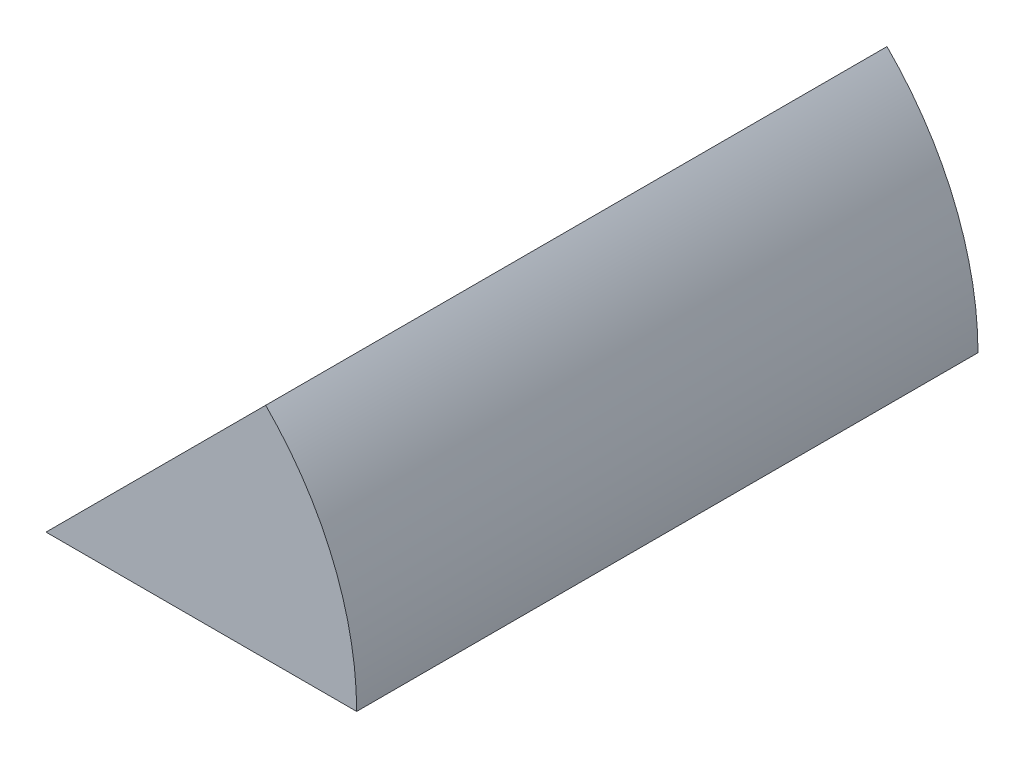
SolidWorks part; units mm, degrees
ref_plane "Alzado" through (0, 0, 0) normal (0, 0, 1) x (1, 0, 0)
ref_plane "Planta" through (0, 0, 0) normal (0, 1, 0) x (1, 0, 0)
ref_plane "Vista lateral" through (0, 0, 0) normal (1, 0, 0) x (0, 0, -1)
sketch "Croquis1" plane through (0, 0, 0) normal (0, 0, 1) x (1, 0, 0)
  line L1 (0, 0) -> (25, 0)
  line L2 (0, 0) -> (17.6777, 17.6777)
  arc A0 (25, 0) -> (17.6777, 17.6777) centre (0, 0) ccw
  dimension "D1" = 50
  dimension "D2" = 45
extrude "Saliente-Extruir1" add sketch "Croquis1" along normal blind 50
sketch "Croquis2" plane through (0, 0, 0) normal (0, 0, -1) x (-1, 0, 0)
  circle A0 centre (-16.6723, 6.6741) radius 5
  dimension "D1" = 10
extrude "Cortar-Extruir1" cut sketch "Croquis2" against normal blind 10 contours A0
